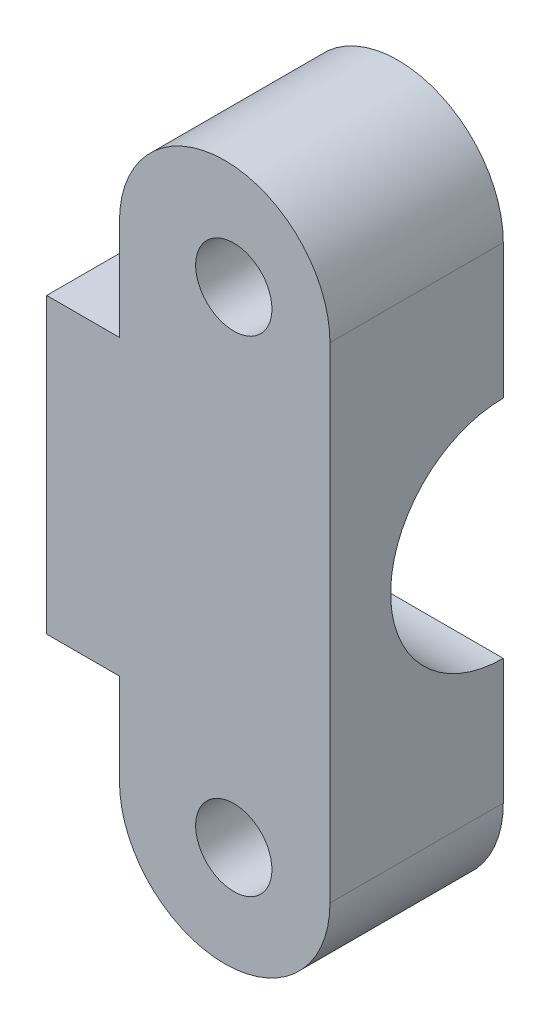
SolidWorks part; units mm, degrees
ref_plane "Plan de face" through (0, 0, 0) normal (0, 0, 1) x (1, 0, 0)
ref_plane "Plan de dessus" through (0, 0, 0) normal (0, 1, 0) x (1, 0, 0)
ref_plane "Plan de droite" through (0, 0, 0) normal (1, 0, 0) x (0, 0, -1)
sketch "Esquisse1" plane through (0, 0, 0) normal (0, 0, 1) x (1, 0, 0)
  line L0 (-15.7923, 40.455) -> (-15.7923, 54.455)
  line L2 (-21.864, 43.0863) -> (-21.864, 40.455)
  line L3 (-21.864, 51.5474) -> (-23.963, 51.5474)
  line L6 (-21.864, 50.3828) -> (-15.2684, 50.3828)
  line L7 (-15.2684, 50.3828) -> (-15.2684, 53.756)
  line L8 (-15.2684, 53.756) -> (-13.4301, 53.756)
  line L9 (-15.2684, 56.9518) -> (-16.9279, 55.9972)
  line L10 (-20.8162, 54.455) -> (-21.864, 54.455)
  line L11 (-21.864, 54.455) -> (-21.864, 50.3828)
  line L12 (-21.864, 43.0863) -> (-23.963, 43.0863)
  line L13 (-23.963, 51.5474) -> (-23.963, 43.0863)
  line L17 (-21.864, 54.455) -> (-21.864, 51.5474)
  arc A0 (-15.7923, 54.455) -> (-21.864, 54.455) centre (-18.8282, 54.455) ccw
  circle A1 centre (-18.5662, 40.455) radius 1.1 construction
  arc A2 (-13.4301, 53.756) -> (-15.2684, 56.9518) centre (-13.2309, 55.9972) ccw
  arc A3 (-16.9279, 55.9972) -> (-20.8162, 54.455) centre (-18.5662, 54.455) ccw
  arc A4 (-21.864, 40.455) -> (-15.7923, 40.455) centre (-18.8282, 40.455) ccw
  circle A5 centre (-18.5662, 54.455) radius 1.1 construction
  circle A6 centre (-18.5662, 40.455) radius 1.1
  circle A7 centre (-18.5662, 54.455) radius 1.1
  dimension "D1" = 0
extrude "Extrusion1" add sketch "Esquisse1" along normal blind 5
sketch "Esquisse2" plane through (-23.963, 0, 0) normal (-1, 0, 0) x (0, 0, 1)
  line L0 (0, 51.5474) -> (0, 43.0863) construction
  circle A0 centre (0, 47.3169) radius 3.25
  dimension "D1" = 6.5
extrude "Enlèv. mat.-Extru.1" cut sketch "Esquisse2" against normal through all
